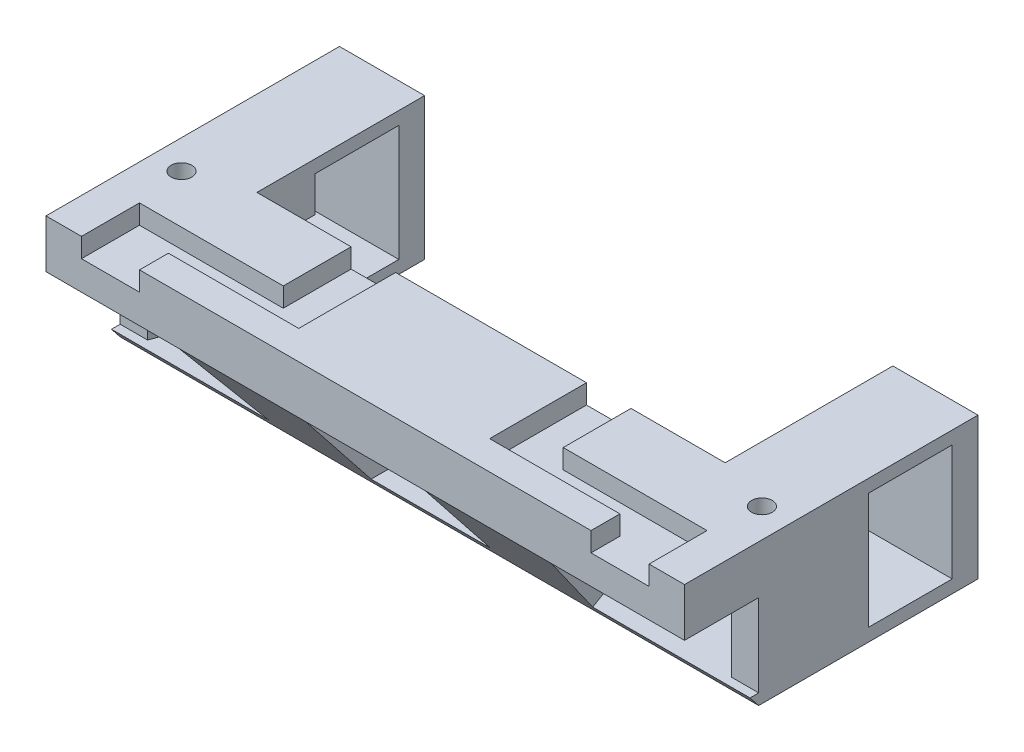
SolidWorks part; units mm, degrees
ref_plane "Alzado" through (0, 0, 0) normal (0, 0, 1) x (1, 0, 0)
ref_plane "Planta" through (0, 0, 0) normal (0, 1, 0) x (1, 0, 0)
ref_plane "Vista lateral" through (0, 0, 0) normal (1, 0, 0) x (0, 0, -1)
sketch "Croquis1" plane through (0, 0, 0) normal (0, 1, 0) x (1, 0, 0)
  line L1 (-38.8235, 22.2022) -> (60.1765, 22.2022)
  line L2 (-38.8235, 22.2022) -> (-38.8235, -26.7978)
  line L3 (-38.8235, -26.7978) -> (60.1765, -26.7978)
  line L4 (60.1765, 22.2022) -> (60.1765, -26.7978)
  dimension "D1" = 99
  dimension "D2" = 49
extrude "Saliente-Extruir1" add sketch "Croquis1" along normal blind 22
sketch "Croquis2" plane through (-38.8235, 0, 0) normal (-1, 0, 0) x (0, 0, 1)
  line L20 (-18.2022, 20) -> (-18.2022, 2)
  line L24 (-18.2022, 2) -> (-5.2022, 2)
  line L26 (-18.2022, 20) -> (-5.2022, 20)
  line L27 (-18.2022, 20) -> (-18.2022, 2)
  line L28 (-18.2022, 2) -> (-5.2022, 2)
  line L29 (-5.2022, 20) -> (-5.2022, 2)
  dimension "D3" = 18
  dimension "D4" = 13
extrude "Cortar-Extruir1" cut sketch "Croquis2" against normal through all contours L29 L26 L20 L24
sketch "Croquis3" plane through (-38.8235, 0, 0) normal (-1, 0, 0) x (0, 0, 1)
  line L0 (-22.2022, 0) -> (26.7978, 0) construction
  line L6 (23.2978, 0) -> (26.7978, 0)
  line L7 (23.2978, 0) -> (23.2978, 22)
  line L8 (23.2978, 22) -> (26.7978, 22)
  line L9 (26.7978, 0) -> (26.7978, 22)
extrude "Cortar-Extruir2" cut sketch "Croquis3" against normal through all
sketch "Croquis4" plane through (0, 22, 0) normal (0, 1, 0) x (1, 0, 0)
  line L0 (60.1765, 22.2022) -> (-38.8235, 22.2022) construction
  line L4 (46.9765, 22.2022) -> (46.9765, -3.7978)
  line L5 (46.9765, -3.7978) -> (-25.6235, -3.7978)
  line L6 (46.9765, -3.7978) -> (46.9765, 22.2022)
  line L7 (46.9765, 22.2022) -> (-25.6235, 22.2022)
  line L8 (-25.6235, -3.7978) -> (-25.6235, 22.2022)
  line L13 (-25.6235, 22.2022) -> (-25.6235, -3.7978)
  line M15 (60.1765, 22.2022) -> (-38.8235, 22.2022)
  dimension "D3" = 26
extrude "Cortar-Extruir3" cut sketch "Croquis4" against normal through all contours L8 L5 L4 M15
sketch "Croquis6" plane through (0, 0, 23.2978) normal (0, 0, 1) x (1, 0, 0)
  line L0 (60.1765, 22) -> (-38.8235, 22) construction
  line L1 (60.1765, 0) -> (10.6765, 0)
  line L2 (60.1765, 0) -> (60.1765, 22)
  line L3 (60.1765, 22) -> (10.6765, 22)
  line L4 (10.6765, 0) -> (10.6765, 1.7)
  line L6 (-38.8235, 22) -> (10.6765, 22)
  line L7 (-38.8235, 22) -> (-38.8235, 0)
  line L8 (-38.8235, 0) -> (10.6765, 0)
  line L9 (10.6765, 1.7) -> (10.6765, 0)
  line L12 (10.6765, 22) -> (1.4265, 22)
  line L14 (10.6765, 1.7) -> (1.4265, 1.7)
  line L17 (1.4265, 1.7) -> (1.4265, 14.5)
  line L18 (10.6765, 1.7) -> (19.9265, 1.7)
  line L21 (19.9265, 1.7) -> (19.9265, 14.5)
  line L22 (19.9265, 1.7) -> (19.9265, 14.5)
  line L23 (19.9265, 14.5) -> (1.4265, 14.5)
  dimension "D1" = 49.5
  dimension "D2" = 7.5
  dimension "D3" = 12.8
  dimension "D4" = 9.25
  dimension "D5" = 9.25
extrude "Cortar-Extruir4" cut sketch "Croquis6" against normal through all contours L21 L23 L17 L14 L18
sketch "Croquis7" plane through (0, 0, 23.2978) normal (0, 0, 1) x (1, 0, 0)
  line L0 (19.9265, 14.5) -> (60.1765, 14.5) construction
  line L1 (60.1765, 22) -> (60.1765, 0) construction
  line L11 (60.1765, 14.5) -> (39.5415, 14.5)
  line L12 (60.1765, 14.5) -> (60.1765, 1.7)
  line L13 (60.1765, 1.7) -> (39.5415, 1.7)
  line L14 (39.5415, 14.5) -> (39.5415, 1.7)
  dimension "D2" = 12.8
sketch "Croquis11" plane through (0, 0, 0) normal (0, -1, 0) x (1, 0, 0)
  line L0 (54.1765, 23.2978) -> (46.9765, 3.7978)
  line L1 (60.1765, 23.2978) -> (-38.8235, 23.2978) construction
extrude "Cortar-Extruir7" cut sketch "Croquis7" along direction (-0.3464, 0, -0.9381) on the side against the normal blind 60
sketch "Croquis12" plane through (0, 0, 23.2978) normal (0, 0, 1) x (1, 0, 0)
  line L0 (-38.8235, 22) -> (-38.8235, 0) construction
  line L1 (-38.8235, 14.5) -> (-18.2235, 14.5)
  line L2 (-38.8235, 14.5) -> (-38.8235, 1.7)
  line L4 (-18.2235, 14.5) -> (-18.2235, 1.7)
  line L6 (-38.8235, 1.7) -> (-17.9068, 1.7)
  dimension "D2" = 20.6
  dimension "D3" = 12.8
sketch "Croquis13" plane through (0, 0, 0) normal (0, -1, 0) x (1, 0, 0)
  line L1 (-25.6235, 3.7978) -> (-32.8235, 23.2978)
  line L2 (-38.8235, 23.2978) -> (-17.9068, 23.2978) construction
extrude "Cortar-Extruir8" cut sketch "Croquis12" along direction (-0.3464, 0, 0.9381) on the side against the normal blind 60
sketch "Croquis15" plane through (-38.8235, 0, 0) normal (-1, 0, 0) x (0, 0, 1)
  line L0 (-22.2022, 22) -> (23.2978, 22) construction
  line L3 (-5.2022, 22) -> (11.7978, 22)
  line L5 (23.2978, 14.5) -> (23.2978, 1.7) construction
  line L11 (-22.2022, 0) -> (23.2978, 0) construction
  line L12 (23.2978, 0) -> (11.7978, 0)
  line L13 (23.2978, 0) -> (23.2978, 14.5)
  line L14 (11.7978, 0) -> (23.2978, 14.5)
extrude "Cortar-Extruir9" cut sketch "Croquis15" against normal through all both and the other way through all
sketch "Croquis16" plane through (-38.8235, 0, 0) normal (-1, 0, 0) x (0, 0, 1)
  line L1 (23.2978, 14.5) -> (11.7978, 14.5)
  line L2 (23.2978, 14.5) -> (23.2978, 1.7)
  line L4 (11.7978, 14.5) -> (11.7978, 1.7)
  line L7 (23.2978, 1.7) -> (11.7978, 1.7)
extrude "Cortar-Extruir11" cut sketch "Croquis16" against normal blind 10
sketch "Croquis17" plane through (60.1765, 0, 0) normal (1, 0, 0) x (0, 0, -1)
  line L1 (-23.2978, 14.5) -> (-11.7978, 14.5)
  line L4 (-11.7978, 14.5) -> (-11.7978, 1.7)
  line L7 (-11.7978, 1.7) -> (-23.2978, 1.7)
  line L8 (-23.2978, 14.5) -> (-23.2978, 1.7)
extrude "Cortar-Extruir12" cut sketch "Croquis17" against normal blind 10
sketch "Croquis18" plane through (0, 22, 0) normal (0, 1, 0) x (1, 0, 0)
  line L0 (60.1765, -23.2978) -> (-38.8235, -23.2978) construction
  line L4 (-24.3235, -23.2978) -> (-24.3235, -18.8184)
  line L5 (-24.3235, -18.8184) -> (-4.1205, -18.8184)
  line L6 (10.6765, -23.2978) -> (45.6765, -23.2978)
  line L9 (45.6765, -23.2978) -> (45.6765, -18.8184)
  line L10 (-24.3235, -23.2978) -> (-33.3235, -23.2978)
  line L11 (-24.3235, -23.2978) -> (-24.3235, -18.8184)
  line L13 (-33.3235, -23.2978) -> (-33.3235, -18.8184)
  line L14 (45.6765, -23.2978) -> (54.6765, -23.2978)
  line L15 (45.6765, -23.2978) -> (45.6765, -18.8184)
  line L17 (54.6765, -23.2978) -> (54.6765, -18.8184)
  line L18 (-4.1205, -18.8184) -> (-4.1205, -3.7978)
  line L19 (46.9765, -3.7978) -> (-25.6235, -3.7978) construction
  line L20 (-4.1205, -3.7978) -> (-11.0235, -3.7978)
  line L21 (-11.0235, -3.7978) -> (-11.0235, -14.3071)
  line L22 (-11.0235, -14.3071) -> (-33.3235, -14.3071)
  line L23 (-33.3235, -14.3071) -> (-33.3235, -18.8184)
  line L24 (-4.1205, -3.7978) -> (-11.0235, -3.7978)
  line L25 (25.4765, -3.7978) -> (32.3765, -3.7978)
  line L26 (45.6765, -18.8184) -> (25.4765, -18.8184)
  line L27 (25.4765, -18.8184) -> (25.4765, -3.7978)
  line L28 (32.3765, -3.7978) -> (32.3765, -14.3071)
  line L29 (32.3765, -14.3071) -> (54.6765, -14.3071)
  line L30 (54.6765, -14.3071) -> (54.6765, -18.8184)
  line M18 (46.9765, -3.7978) -> (-25.6235, -3.7978)
  line M22 (-38.8235, -23.2978) -> (60.1765, -23.2978)
  dimension "D1" = 35
  dimension "D2" = 35
  dimension "D3" = 9
  dimension "D4" = 9
  dimension "D6" = 6.9
extrude "Cortar-Extruir13" cut sketch "Croquis18" against normal blind 3 contours L22 L23 L13 L4 L5 L18 L21 M22 M18 | L30 L29 L28 L27 L26 L9 L17 M18 M22
sketch "Croquis20" plane through (0, 0, 0) normal (0, -1, 0) x (1, 0, 0)
  line L0 (-38.8235, 11.7978) -> (-38.8235, 6.7978) construction
  line L1 (-38.8235, -22.2022) -> (-38.8235, 11.7978) construction
  line L2 (-35.9235, 6.7978) -> (57.2765, 6.7978) construction
  circle A0 centre (-34.3235, 6.7978) radius 1.6
  circle A1 centre (55.6765, 6.7978) radius 1.6
  dimension "D4" = 3.2
  dimension "D5" = 3.2
  dimension "D1" = 5
  dimension "D2" = 4.5
extrude "Cortar-Extruir14" cut sketch "Croquis20" against normal through all both and the other way through all
sketch "Croquis21" plane through (0, 22, 0) normal (0, 1, 0) x (1, 0, 0)
  line L0 (-34.3235, -8.3978) -> (-34.3235, -23.2978)
  line L1 (-33.3235, -23.2978) -> (-38.8235, -23.2978) construction
  line L2 (-34.3235, -6.7978) -> (-38.8235, -6.7978)
  line L3 (-38.8235, 22.2022) -> (-38.8235, -23.2978) construction
  line L4 (-35.9235, -6.7978) -> (-38.8235, -6.7978)
  line L5 (55.6765, -6.7978) -> (60.1765, -6.7978)
  line L6 (60.1765, -23.2978) -> (60.1765, 22.2022) construction
  line L7 (55.6765, -6.7978) -> (55.6765, -23.2978) construction
  line L8 (60.1765, -23.2978) -> (54.6765, -23.2978) construction
  circle A0 centre (-34.3235, -6.7978) radius 1.6 construction
